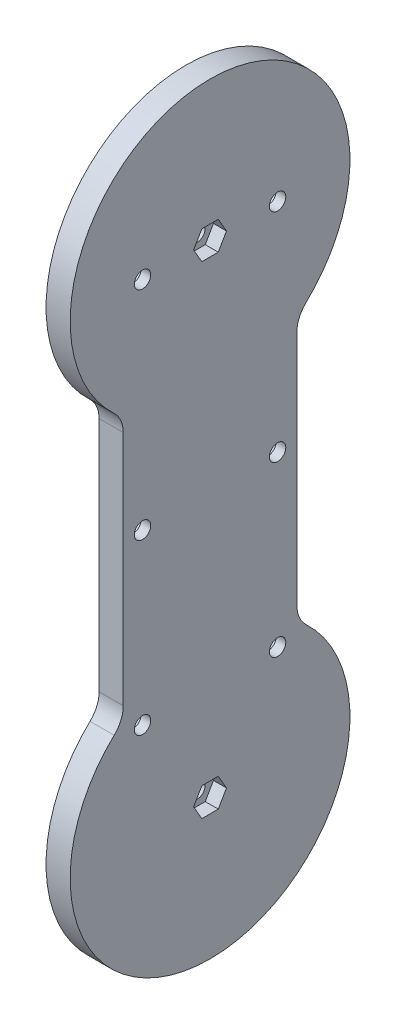
SolidWorks part; units mm, degrees
ref_plane "Front Plane" through (0, 0, 0) normal (0, 0, 1) x (1, 0, 0)
ref_plane "Top Plane" through (0, 0, 0) normal (0, 1, 0) x (1, 0, 0)
ref_plane "Right Plane" through (0, 0, 0) normal (1, 0, 0) x (0, 0, -1)
sketch "Sketch1" plane through (0, 0, 0) normal (1, 0, 0) x (0, 0, -1)
  line L0 (-32, 127.9755) -> (-32, 177.0245)
  line L1 (4, 177.0245) -> (4, 127.9755)
  arc A0 (5.8857, 123.6083) -> (-33.8857, 123.6083) centre (-14, 102.5) cw
  arc A1 (-33.8857, 123.6083) -> (-32, 127.9755) centre (-38, 127.9755) ccw
  arc A2 (-32, 177.0245) -> (-33.8857, 181.3917) centre (-38, 177.0245) ccw
  arc A3 (-33.8857, 181.3917) -> (5.8857, 181.3917) centre (-14, 202.5) cw
  arc A4 (5.8857, 181.3917) -> (4, 177.0245) centre (10, 177.0245) ccw
  arc A5 (4, 127.9755) -> (5.8857, 123.6083) centre (10, 127.9755) ccw
extrude "Plate B" add sketch "Sketch1" along normal blind 5 from offset 27.05
sketch "Sketch2" plane through (0, 0, 0) normal (1, 0, 0) x (0, 0, -1)
  circle A0 centre (-14, 102.5) radius 7.25
  circle A1 centre (-14, 202.5) radius 7.25
extrude "Pin seats" cut sketch "Sketch2" along normal blind 1.2 from offset 27.25
sketch "Sketch3" plane through (0, 0, 0) normal (1, 0, 0) x (0, 0, -1)
  circle A0 centre (-14, 102.5) radius 1.7
  circle A1 centre (-14, 202.5) radius 1.7
  circle A2 centre (0, 122.5) radius 1.7
  circle A3 centre (-28, 122.5) radius 1.7
  circle A4 centre (0, 157.5) radius 1.7
  circle A5 centre (-28, 157.5) radius 1.7
  circle A6 centre (0, 202.5) radius 1.7
  circle A7 centre (-28, 202.5) radius 1.7
extrude "Bolt holes" cut sketch "Sketch3" along normal blind 5.4 from offset 27.25
sketch "Sketch4" plane through (0, 0, 0) normal (1, 0, 0) x (0, 0, -1)
  line L0 (-15.7032, 105.45) -> (-17.4064, 102.5)
  line L1 (-17.4064, 102.5) -> (-15.7032, 99.55)
  line L2 (-15.7032, 99.55) -> (-12.2968, 99.55)
  line L3 (-12.2968, 99.55) -> (-10.5936, 102.5)
  line L4 (-10.5936, 102.5) -> (-12.2968, 105.45)
  line L5 (-12.2968, 105.45) -> (-15.7032, 105.45)
  line L6 (-15.7032, 205.45) -> (-17.4064, 202.5)
  line L7 (-17.4064, 202.5) -> (-15.7032, 199.55)
  line L8 (-15.7032, 199.55) -> (-12.2968, 199.55)
  line L9 (-12.2968, 199.55) -> (-10.5936, 202.5)
  line L10 (-10.5936, 202.5) -> (-12.2968, 205.45)
  line L11 (-12.2968, 205.45) -> (-15.7032, 205.45)
extrude "Pin nuts" cut sketch "Sketch4" along normal blind 2.9 from offset 24.75
sketch "Sketch5" plane through (0, 0, 0) normal (1, 0, 0) x (0, 0, -1)
  circle A0 centre (0, 122.5) radius 3.2
  circle A1 centre (-28, 122.5) radius 3.2
  circle A2 centre (0, 157.5) radius 3.2
  circle A3 centre (-28, 157.5) radius 3.2
  circle A4 centre (0, 202.5) radius 3.2
  circle A5 centre (-28, 202.5) radius 3.2
extrude "Counterbores" cut sketch "Sketch5" along normal blind 3.2 from offset 27.25
